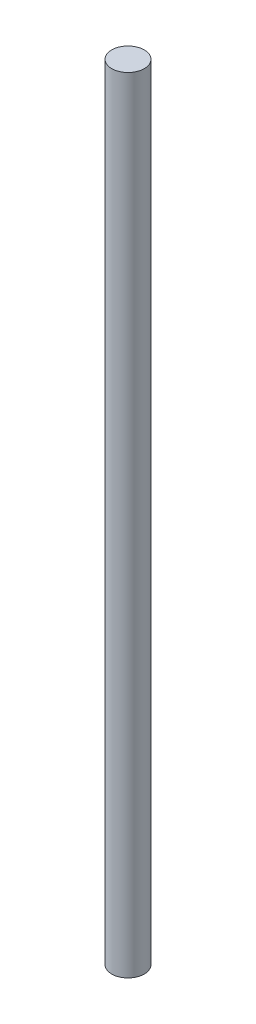
SolidWorks part; units mm, degrees
ref_plane "Front Plane" through (0, 0, 0) normal (0, 0, 1) x (1, 0, 0)
ref_plane "Top Plane" through (0, 0, 0) normal (0, 1, 0) x (1, 0, 0)
ref_plane "Right Plane" through (0, 0, 0) normal (1, 0, 0) x (0, 0, -1)
sketch "Sketch1" plane through (0, 0, 0) normal (0, 1, 0) x (1, 0, 0)
  circle A0 centre (0, 0) radius 2.5
  dimension "D1" = 5
extrude "Boss-Extrude1" add sketch "Sketch1" along normal blind 120.65
